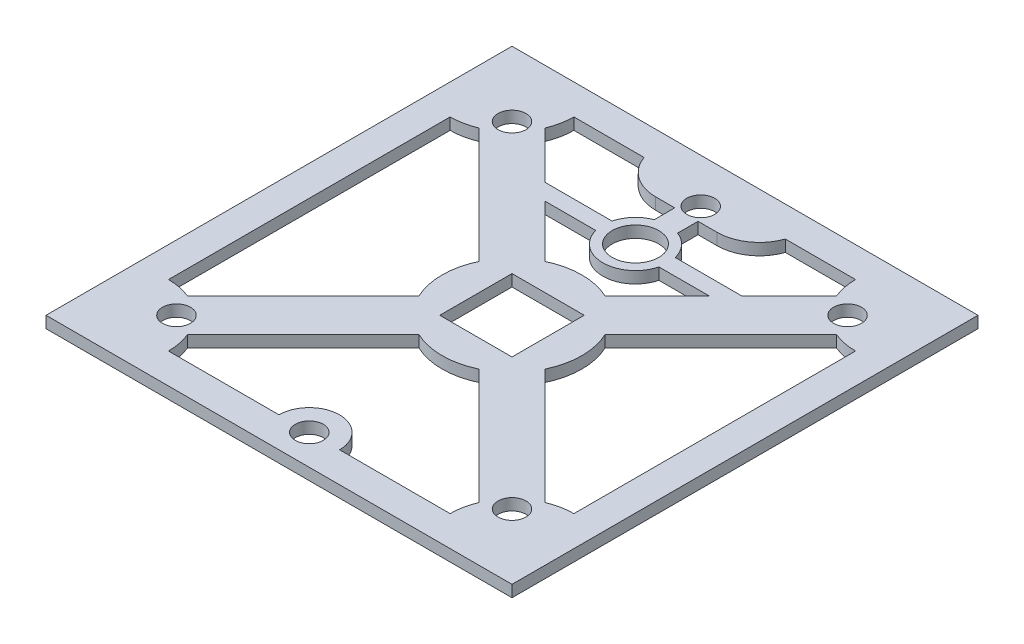
SolidWorks part; units mm, degrees
ref_plane "Front Plane" through (0, 0, 0) normal (0, 0, 1) x (1, 0, 0)
ref_plane "Top Plane" through (0, 0, 0) normal (0, 1, 0) x (1, 0, 0)
ref_plane "Right Plane" through (0, 0, 0) normal (1, 0, 0) x (0, 0, -1)
sketch "Sketch1" plane through (0, 0, 0) normal (0, 1, 0) x (1, 0, 0)
  line L1 (-50, -50) -> (50, -50)
  line L2 (-50, -50) -> (-50, 50)
  line L3 (-50, 50) -> (50, 50)
  line L4 (50, -50) -> (50, 50)
  line L5 (-50, -50) -> (50, 50) construction
  line L6 (-50, 50) -> (50, -50) construction
  point P0 (0, 0)
  dimension "D1" = 100
extrude "Boss-Extrude1" add sketch "Sketch1" along normal blind 2.5
sketch "Sketch5" plane through (0, 2.5, 0) normal (0, 1, 0) x (1, 0, 0)
  line L1 (-43.5, -43.5) -> (43.5, -43.5)
  line L2 (-43.5, -43.5) -> (-43.5, 43.5)
  line L3 (-43.5, 43.5) -> (43.5, 43.5)
  line L4 (43.5, -43.5) -> (43.5, 43.5)
  line L5 (-43.5, -43.5) -> (43.5, 43.5) construction
  line L6 (-43.5, 43.5) -> (43.5, -43.5) construction
  line L7 (50, -50) -> (50, 50) construction
  line L8 (-50, -50) -> (50, -50) construction
  point P0 (0, 0)
  dimension "D1" = 6.5
  dimension "D2" = 6.5
extrude "Cut-Extrude2" cut sketch "Sketch5" against normal blind 4
sketch "Sketch6" plane through (0, 2.5, 0) normal (0, 1, 0) x (1, 0, 0)
  circle A0 centre (0, 0) radius 15
  dimension "D1" = 30
extrude "Boss-Extrude3" add sketch "Sketch6" against normal blind 2.5 separate body
sketch "Sketch7" plane through (0, 2.5, 0) normal (0, 1, 0) x (1, 0, 0)
  line L1 (-7.75, -7.75) -> (7.75, -7.75)
  line L2 (-7.75, -7.75) -> (-7.75, 7.75)
  line L3 (-7.75, 7.75) -> (7.75, 7.75)
  line L4 (7.75, -7.75) -> (7.75, 7.75)
  line L5 (-7.75, -7.75) -> (7.75, 7.75) construction
  line L6 (-7.75, 7.75) -> (7.75, -7.75) construction
  point P0 (0, 0)
  dimension "D1" = 15.5
  dimension "D2" = 15.5
extrude "Cut-Extrude3" cut sketch "Sketch7" against normal blind 2.5
sketch "Sketch8" plane through (0, 2.5, 0) normal (0, 1, 0) x (1, 0, 0)
  line L0 (43.5, -43.5) -> (43.5, 43.5) construction
  line L1 (43.5, 43.5) -> (-43.5, 43.5) construction
  line L2 (0, -54.2426) -> (0, 54.2426)
  line L3 (30.2201, 43.5) -> (43.5, 43.5)
  line L4 (43.5, 43.5) -> (43.5, 30.2201)
  line L5 (-63.2717, 0) -> (63.2717, 0)
  arc A0 (43.5, 30.2201) -> (30.2201, 43.5) centre (43.5, 43.5) cw
  arc A1 (-43.5, 30.2201) -> (-30.2201, 43.5) centre (-43.5, 43.5) ccw
  arc A2 (43.5, -30.2201) -> (30.2201, -43.5) centre (43.5, -43.5) ccw
  arc A3 (-43.5, -30.2201) -> (-30.2201, -43.5) centre (-43.5, -43.5) cw
  point P13 (0, 0)
  point P15 (0, 0)
  line M3 (-43.5, 43.5) -> (43.5, 43.5)
  line M4 (43.5, 43.5) -> (43.5, -43.5)
  line M5 (43.5, -43.5) -> (-43.5, -43.5)
  line M6 (-43.5, -43.5) -> (-43.5, 43.5)
extrude "Boss-Extrude4" add sketch "Sketch8" against normal blind 2.5 contours A3 M6 M5 | A1 M6 M3 | A0 M4 M3 | A2 M4 M5
sketch "Sketch9" plane through (0, 2.5, 0) normal (0, 1, 0) x (1, 0, 0)
  line L0 (7.75, -7.75) -> (38.0042, -38.0042)
  line L2 (-7.75, -7.75) -> (-38.0042, -38.0042)
  line L4 (7.75, 7.75) -> (38.0042, 38.0042)
  line L5 (-7.75, 7.75) -> (-38.0042, 38.0042)
  point P17 (0, 0)
  point P22 (0, 0)
extrude "Extrude-Thin2" add sketch "Sketch9" against normal blind 2.5 thin thin type mid plane wall 10
sketch "Sketch10" plane through (0, 2.5, 0) normal (0, 1, 0) x (1, 0, 0)
  line L0 (50, 50) -> (-50, 50) construction
  line L1 (50, -50) -> (50, 50) construction
  line L2 (-81.3718, 0) -> (93.495, 0) construction
  line L3 (0, 82.8678) -> (0, -87.0228) construction
  circle A0 centre (36, 36) radius 3
  circle A1 centre (-36, 36) radius 3
  circle A2 centre (36, -36) radius 3
  circle A3 centre (-36, -36) radius 3
  dimension "D1" = 6
  dimension "D2" = 14
  dimension "D3" = 14
extrude "Cut-Extrude5" cut sketch "Sketch10" against normal blind 2.5
sketch "Sketch11" plane through (0, 2.5, 0) normal (0, 1, 0) x (1, 0, 0)
  line L0 (-30.2201, -43.5) -> (30.2201, -43.5) construction
  line L1 (-84.2761, 0) -> (68.5897, 0) construction
  circle A0 centre (0, -43.5) radius 6.5
  circle A1 centre (0, 43.5) radius 6.5
  dimension "D1" = 13
extrude "Boss-Extrude5" add sketch "Sketch11" against normal blind 2.5
sketch "Sketch12" plane through (0, 2.5, 0) normal (0, 1, 0) x (1, 0, 0)
  line L0 (-73.9637, 0) -> (62.8734, 0) construction
  circle A0 centre (0, 43.5) radius 3
  circle A1 centre (0, -43.5) radius 3
  dimension "D1" = 6
extrude "Cut-Extrude6" cut sketch "Sketch12" against normal blind 3
sketch "Sketch13" plane through (0, 2.5, 0) normal (0, 1, 0) x (1, 0, 0)
  line L0 (0, 15) -> (0, 43.5) construction
  arc A0 (6.4645, 13.5355) -> (-6.4645, 13.5355) centre (0, 0) ccw construction
  circle A1 centre (0, 26.5) radius 5
  arc A2 (-6.5, 43.5) -> (6.5, 43.5) centre (0, 43.5) ccw construction
  circle A3 centre (0, 26.5) radius 7
  dimension "D1" = 17
  dimension "D2" = 10
  dimension "D3" = 2
extrude "Boss-Extrude6" add sketch "Sketch13" against normal blind 2.5 separate body
sketch "Sketch14" plane through (0, 0, 0) normal (0, -1, 0) x (-1, 0, 0)
  line L0 (0, 31.5) -> (0, 40.5)
  circle A0 centre (0, 26.5) radius 5 construction
  circle A1 centre (0, 43.5) radius 3 construction
extrude "Extrude-Thin5" add sketch "Sketch14" against normal blind 2.5 thin contours L0 thin type mid plane wall 5
sketch "Sketch15" plane through (0, 0, 0) normal (0, -1, 0) x (-1, 0, 0)
  line L0 (0, 6.9382) -> (0, 43.7947) construction
  line L2 (-5.4315, 26.5) -> (-22.5267, 26.5)
  line L3 (5.4315, 26.5) -> (22.5267, 26.5)
extrude "Extrude-Thin7" add sketch "Sketch15" against normal blind 2.5 thin thin type mid plane wall 3.5
sketch "Sketch17" plane through (0, 0, 0) normal (0, -1, 0) x (-1, 0, 0)
  line L0 (6.5914, 46.5) -> (-6.5914, 46.5) construction
  line L1 (6.5914, 37.4259) -> (-6.5914, 37.4259)
  line L2 (6.5914, 55.5741) -> (-6.5914, 55.5741)
  circle A0 centre (0, 43.5) radius 3 construction
  arc A1 (6.5914, 37.4259) -> (6.5914, 55.5741) centre (6.5914, 46.5) ccw
  arc A2 (-6.5914, 55.5741) -> (-6.5914, 37.4259) centre (-6.5914, 46.5) ccw
  point P4 (0, 46.5)
  point P9 (0, 43.5)
  point P10 (15.1105, 33.884)
extrude "Boss-Extrude8" add sketch "Sketch17" against normal blind 2.5
sketch "Sketch20" plane through (0, 0, 0) normal (0, -1, 0) x (-1, 0, 0)
  line L0 (-50, 50) -> (-14.9633, 50) construction
  line L1 (14.9633, 50) -> (-16.1193, 50)
  line L2 (14.9633, 50) -> (14.9633, 56.049)
  line L3 (14.9633, 56.049) -> (-16.1193, 56.049)
  line L4 (-16.1193, 50) -> (-16.1193, 56.049)
  arc A0 (6.5914, 37.4259) -> (15.1552, 43.5) centre (6.5914, 46.5) ccw construction
extrude "Cut-Extrude8" cut sketch "Sketch20" against normal blind 2.5
sketch "Sketch21" plane through (0, 0, 0) normal (0, -1, 0) x (-1, 0, 0)
  line L0 (-56.2379, 0) -> (62.2861, 0) construction
  line L1 (0, -4.3659) -> (0, 58.7515) construction
  line L2 (-50, 50) -> (50, 50) construction
  circle A0 centre (0, 40.5) radius 3
  dimension "D1" = 6
  dimension "D2" = 9.5
extrude "Cut-Extrude9" cut sketch "Sketch21" against normal blind 10
